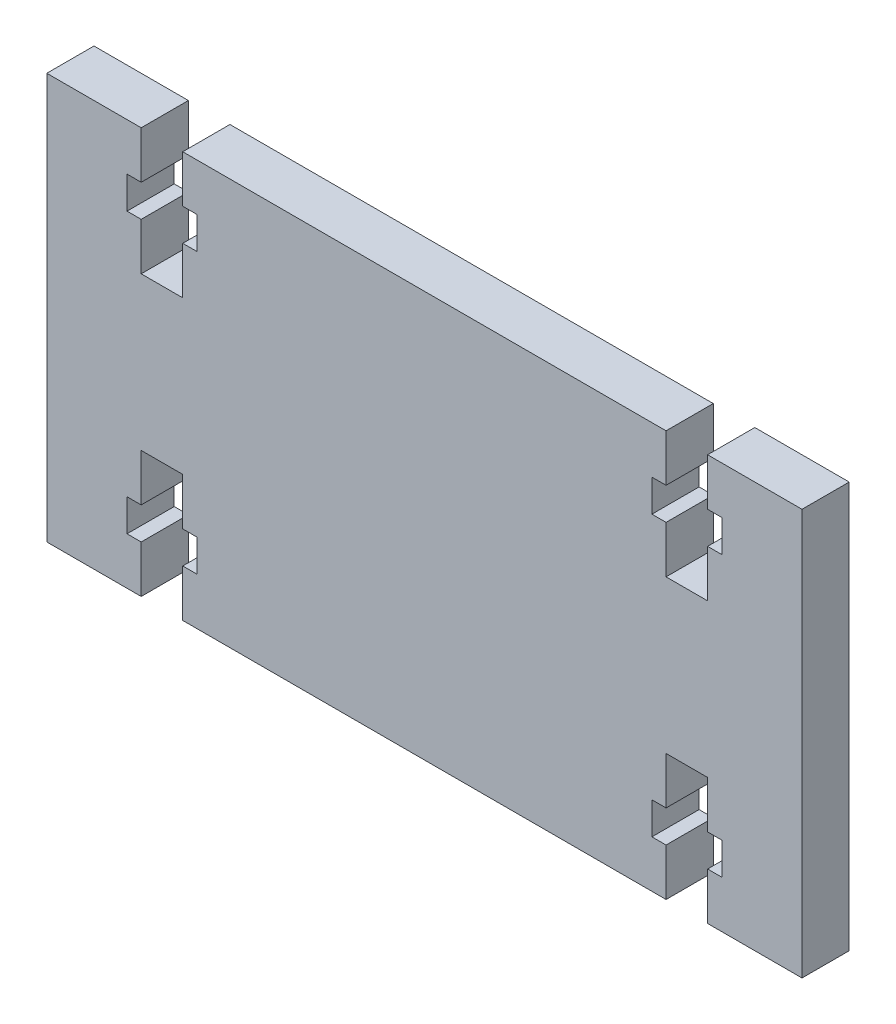
SolidWorks part; units mm, degrees
ref_plane "Front Plane" through (0, 0, 0) normal (0, 0, 1) x (1, 0, 0)
ref_plane "Top Plane" through (0, 0, 0) normal (0, 1, 0) x (1, 0, 0)
ref_plane "Right Plane" through (0, 0, 0) normal (1, 0, 0) x (0, 0, -1)
sketch "Sketch1" plane through (0, 0, 0) normal (0, 0, 1) x (1, 0, 0)
  line L1 (-40, 21.5) -> (40, 21.5)
  line L2 (-40, 21.5) -> (-40, -21.5)
  line L3 (-40, -21.5) -> (40, -21.5)
  line L4 (40, 21.5) -> (40, -21.5)
  dimension "D1" = 80
  dimension "D2" = 40
  dimension "D3" = 43
  dimension "D4" = 21.5
extrude "Boss-Extrude1" add sketch "Sketch1" along normal blind 5
sketch "Sketch3" plane through (0, 0, 5) normal (0, 0, 1) x (1, 0, 0)
  line L12 (30, -21.5) -> (30, -16.5)
  line L13 (-40, -21.5) -> (40, -21.5) construction
  line L14 (30, -16.5) -> (31.5, -16.5)
  line L15 (31.5, -16.5) -> (31.5, -13.1)
  line L16 (31.5, -13.1) -> (30, -13.1)
  line L17 (30, -13.1) -> (30, -8.1)
  line L18 (30, -8.1) -> (25.6, -8.1)
  line L19 (25.6, -8.1) -> (25.6, -13.1)
  line L20 (25.6, -13.1) -> (24.1, -13.1)
  line L21 (24.1, -13.1) -> (24.1, -16.5)
  line L22 (24.1, -16.5) -> (25.6, -16.5)
  line L23 (25.6, -16.5) -> (25.6, -21.5)
  line L24 (25.6, -21.5) -> (30, -21.5)
  line L25 (0, 0) -> (0, 13.3015) construction
  line L26 (0, 0) -> (-15.5658, 0) construction
  line L27 (-25.6, -21.5) -> (-30, -21.5)
  line L28 (-25.6, -16.5) -> (-25.6, -21.5)
  line L29 (-24.1, -16.5) -> (-25.6, -16.5)
  line L30 (-24.1, -13.1) -> (-24.1, -16.5)
  line L31 (-25.6, -13.1) -> (-24.1, -13.1)
  line L32 (-25.6, -8.1) -> (-25.6, -13.1)
  line L33 (-30, -8.1) -> (-25.6, -8.1)
  line L34 (-30, -13.1) -> (-30, -8.1)
  line L35 (-31.5, -13.1) -> (-30, -13.1)
  line L36 (-31.5, -16.5) -> (-31.5, -13.1)
  line L37 (-30, -16.5) -> (-31.5, -16.5)
  line L38 (-30, -21.5) -> (-30, -16.5)
  line L39 (40, -21.5) -> (40, 21.5) construction
  line L40 (25.6, 21.5) -> (30, 21.5)
  line L41 (25.6, 16.5) -> (25.6, 21.5)
  line L42 (24.1, 16.5) -> (25.6, 16.5)
  line L43 (24.1, 13.1) -> (24.1, 16.5)
  line L44 (25.6, 13.1) -> (24.1, 13.1)
  line L45 (25.6, 8.1) -> (25.6, 13.1)
  line L46 (30, 8.1) -> (25.6, 8.1)
  line L47 (30, 13.1) -> (30, 8.1)
  line L48 (31.5, 13.1) -> (30, 13.1)
  line L49 (31.5, 16.5) -> (31.5, 13.1)
  line L50 (30, 16.5) -> (31.5, 16.5)
  line L51 (30, 21.5) -> (30, 16.5)
  line L52 (-30, 21.5) -> (-30, 16.5)
  line L53 (-30, 16.5) -> (-31.5, 16.5)
  line L54 (-31.5, 16.5) -> (-31.5, 13.1)
  line L55 (-31.5, 13.1) -> (-30, 13.1)
  line L56 (-30, 13.1) -> (-30, 8.1)
  line L57 (-30, 8.1) -> (-25.6, 8.1)
  line L58 (-25.6, 8.1) -> (-25.6, 13.1)
  line L59 (-25.6, 13.1) -> (-24.1, 13.1)
  line L60 (-24.1, 13.1) -> (-24.1, 16.5)
  line L61 (-24.1, 16.5) -> (-25.6, 16.5)
  line L62 (-25.6, 16.5) -> (-25.6, 21.5)
  line L63 (-25.6, 21.5) -> (-30, 21.5)
  point P5 (0, 0)
  dimension "D1" = 1.5
  dimension "D2" = 10
  dimension "D5" = 1.5
  dimension "D6" = 4.4
  dimension "D7" = 3.4
  dimension "D8" = 5
  dimension "D9" = 5
extrude "Cut-Extrude1" cut sketch "Sketch3" against normal blind 5
